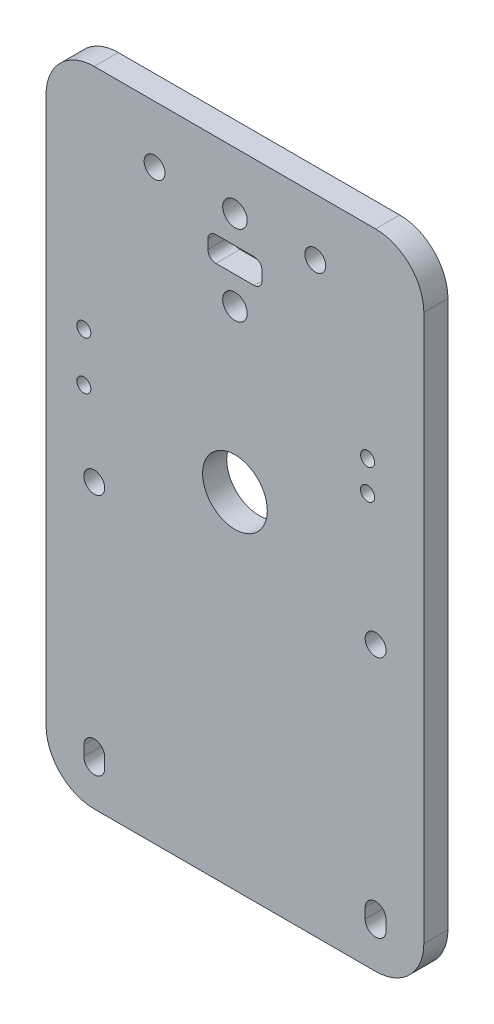
SolidWorks part; units mm, degrees
material "Acrylic (Medium-high impact)"
ref_plane "Спереди" through (0, 0, 0) normal (0, 0, 1) x (1, 0, 0)
ref_plane "Сверху" through (0, 0, 0) normal (0, 1, 0) x (1, 0, 0)
ref_plane "Справа" through (0, 0, 0) normal (1, 0, 0) x (0, 0, -1)
sketch "Model" plane through (0, 0, 0) normal (0, 0, 1) x (1, 0, 0)
  line L5 (0, 170.1561) -> (0, 0) construction
  line L24 (-35, 37.2847) -> (-35, 78.8619) construction
  line L25 (-31.4983, 12.5) -> (-38.4, 12.5) construction
  line L26 (-31.4983, 10) -> (-38.4, 10) construction
  line L27 (-35, 12.5) -> (-35, 10) construction
  line L28 (-32.4, 12.5) -> (-32.4, 10)
  line L29 (-37.6, 12.5) -> (-37.6, 10)
  line L40 (31.4983, 10) -> (38.4, 10) construction
  line L41 (31.4983, 12.5) -> (38.4, 12.5) construction
  line L42 (35, 37.2847) -> (35, 78.8619) construction
  line L43 (35, 12.5) -> (35, 10) construction
  line L44 (32.4, 12.5) -> (32.4, 10)
  line L45 (37.6, 12.5) -> (37.6, 10)
  line L47 (-26.0102, 145.8) -> (26.0946, 145.8) construction
  line L50 (-20, 133.6948) -> (-20, 127.8457) construction
  line L51 (-38.85, 70.45) -> (-29.8907, 70.45) construction
  line L53 (-16.3166, 125.8) -> (17.7871, 125.8) construction
  line L58 (38.85, 70.45) -> (29.8907, 70.45) construction
  line L4875 (-35, 160) -> (35, 160)
  line L4882 (47, 148) -> (47, 12)
  line L4889 (35, 0) -> (-35, 0)
  line L4896 (-47, 12) -> (-47, 148)
  line L6648 (-6.75, 138.9) -> (6.75, 138.9)
  line L6649 (6.75, 138.9) -> (6.75, 132.7)
  line L6650 (6.75, 132.7) -> (-6.75, 132.7)
  line L6651 (-6.75, 132.7) -> (-6.75, 138.9)
  arc A0 (-47, 12) -> (-35, 0) centre (-35, 12) ccw
  arc A1 (35, 0) -> (47, 12) centre (35, 12) ccw
  arc A2 (47, 148) -> (35, 160) centre (35, 148) ccw
  arc A3 (-35, 160) -> (-47, 148) centre (-35, 148) ccw
  arc A13 (-32.4, 12.5) -> (-37.6, 12.5) centre (-35, 12.5) ccw
  arc A14 (-37.6, 10) -> (-32.4, 10) centre (-35, 10) ccw
  arc A19 (32.4, 12.5) -> (37.6, 12.5) centre (35, 12.5) cw
  arc A20 (37.6, 10) -> (32.4, 10) centre (35, 10) cw
  circle A29 centre (0, 145.8) radius 3.05
  circle A30 centre (-20, 145.8) radius 2.6
  circle A31 centre (20, 145.8) radius 2.6
  circle A32 centre (-35, 70.45) radius 2.6
  circle A33 centre (0, 125.8) radius 3.05
  circle A36 centre (35, 70.45) radius 2.6
  point P0 (-6.75, 135.8)
  point P17 (0, 0)
  point P77 (-35, 11.25)
  point P114 (35, 11.25)
  dimension "D29" = 5.2
  dimension "D30" = 5.2
  dimension "D33" = 5.2
  dimension "D35" = 6.1
  dimension "D5" = 5.2
  dimension "D2" = 70
  dimension "D3" = 160
  dimension "D15" = 12
  dimension "D16" = 2.5
  dimension "D17" = 10
  dimension "D18" = 5.2
  dimension "D25" = 14.2
  dimension "D34" = 20
  dimension "D42" = 6.2
  dimension "D9" = 70
  dimension "D10" = 57.95
  dimension "D6" = 20
  dimension "D7" = 20
  dimension "D8" = 13.5
  dimension "D11" = 10
extrude "Base" add sketch "Model" along normal blind 6
sketch "Эскиз1" plane through (0, 0, 0) normal (0, 0, -1) x (-1, 0, 0)
  line L0 (35, 160) -> (-35, 160) construction
  line L1 (0, 160) -> (0, 146.8198) construction
  circle A0 centre (0, 85.8) radius 8.05
  dimension "D2" = 16.1
  dimension "D1" = 74.2
extrude "BearingHole" cut sketch "Эскиз1" against normal blind 10
sketch "Sketch1" plane through (0, 0, 6) normal (0, 0, 1) x (1, 0, 0)
  line L0 (-35, 160) -> (35, 160) construction
  line L1 (47, 148) -> (47, 12) construction
  circle A0 centre (33, 109.5) radius 1.75
  circle A1 centre (33, 102) radius 1.75
  dimension "D1" = 3.5
  dimension "D3" = 7.5
  dimension "D4" = 50.5
  dimension "D5" = 14
extrude "SensorMount" cut sketch "Sketch1" against normal blind 10
sketch "Sketch3" plane through (0, 0, 0) normal (0, 0, -1) x (-1, 0, 0)
  line L0 (-35, 0) -> (35, 0) construction
  line L1 (47, 12) -> (47, 148) construction
  circle A0 centre (37.6, 90.0886) radius 1.75
  circle A1 centre (37.6, 102.0886) radius 1.75
  dimension "D3" = 3.5
  dimension "D4" = 90.0886
  dimension "D1" = 12
  dimension "D2" = 9.4
extrude "CableMount" cut sketch "Sketch3" against normal blind 10
fillet "FilletCableSlot" radius 2 4 edges at (6.75, 138.9, 3) (-6.75, 138.9, 3) (-6.75, 132.7, 3) (6.75, 132.7, 3)
equation "\"D11@Model\"=\"D34@Model\"/2"
